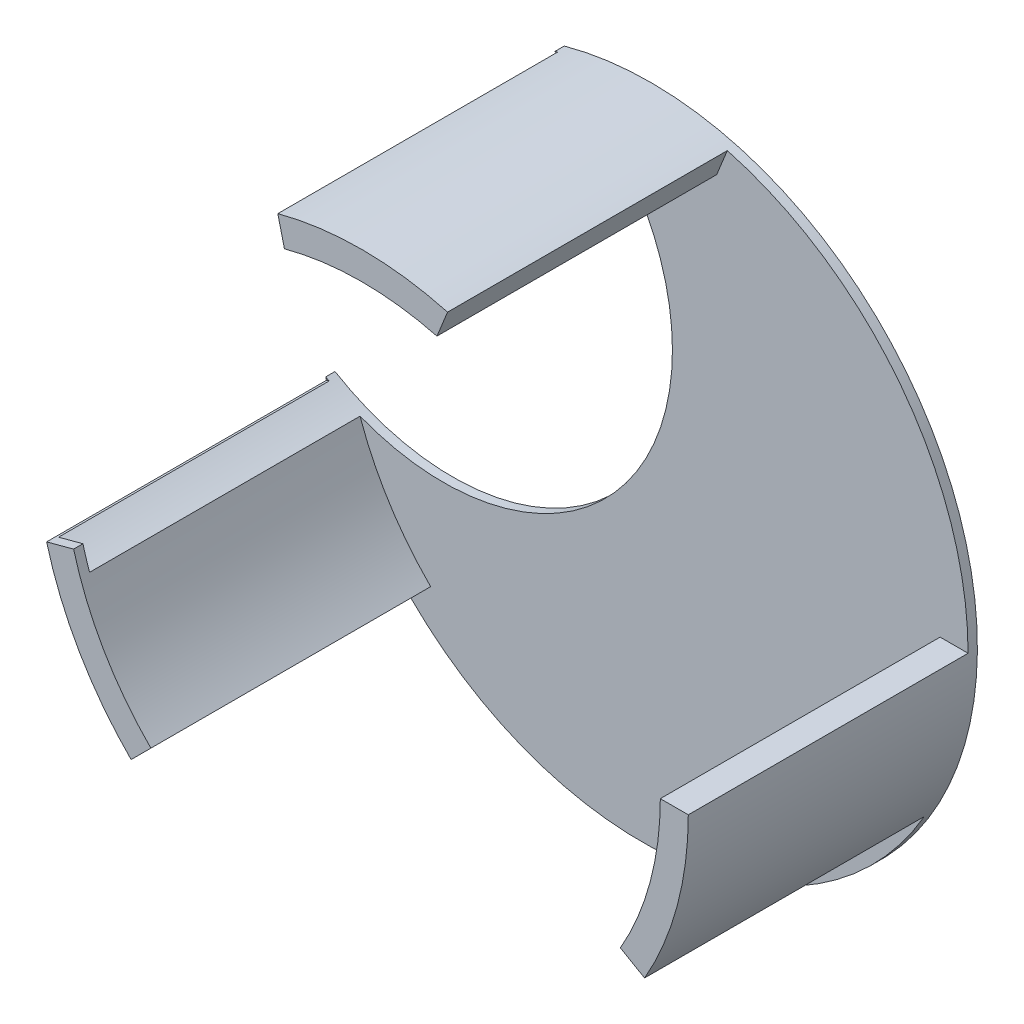
SolidWorks part; units mm, degrees
ref_plane "Front Plane" through (0, 0, 0) normal (0, 0, 1) x (1, 0, 0)
ref_plane "Top Plane" through (0, 0, 0) normal (0, 1, 0) x (1, 0, 0)
ref_plane "Right Plane" through (0, 0, 0) normal (1, 0, 0) x (0, 0, -1)
sketch "Sketch1" plane through (0, 0, 0) normal (0, 0, 1) x (1, 0, 0)
  circle A0 centre (0, 0) radius 17.5
extrude "Boss-Extrude1" add sketch "Sketch1" along normal blind 0.5
sketch "Sketch2" plane through (0, 0, 0.5) normal (0, 0, 1) x (1, 0, 0)
  line L0 (-4.5082, 16.9094) -> (-4.1524, 15.4522)
  line L1 (4.0232, 15.4863) -> (4.593, 16.8865)
  line L2 (-12.3744, -12.3744) -> (-11.3137, -11.3137)
  line L3 (-16.9037, -4.5293) -> (-15.4548, -4.1411)
  line L8 (16, 0) -> (17.5, 0)
  line L9 (17.5, 0) -> (17.5111, -0.0119)
  line L10 (13.8564, -8) -> (15.1554, -8.75)
  line L11 (15.1554, -8.75) -> (15.1816, -8.8208)
  circle A0 centre (0, 0) radius 17.5 construction
  arc A1 (-0.6714, 0) -> (-0.6551, 0.1469) centre (0, 0) cw
  arc A2 (4.593, 16.8865) -> (-4.5082, 16.9094) centre (0, 0) ccw
  arc A3 (-4.1524, 15.4522) -> (4.0232, 15.4863) centre (0, 0) cw
  arc A4 (-12.3744, -12.3744) -> (-16.9037, -4.5293) centre (0, 0) cw
  arc A5 (-15.4548, -4.1411) -> (-11.3137, -11.3137) centre (0, 0) ccw
  arc A7 (13.8564, -8) -> (16, 0) centre (0, 0) ccw
  circle M15 centre (0, 0) radius 17.5
extrude "Boss-Extrude2" add sketch "Sketch2" along normal blind 15 contours A7 L10 L8 M15 | L0 A3 L1 M15 | A5 L2 A4 L3
sketch "Sketch3" plane through (0, 0, 0) normal (0, 0, -1) x (-1, 0, 0)
  line L0 (0, 0) -> (15.15, 8.7595)
  arc A0 (16.9037, -4.5293) -> (4.5082, 16.9094) centre (0, 0) ccw construction
  circle A1 centre (10.6304, 6.1464) radius 12.2794
extrude "Cut-Extrude1" cut sketch "Sketch3" against normal blind 15 contours A1
